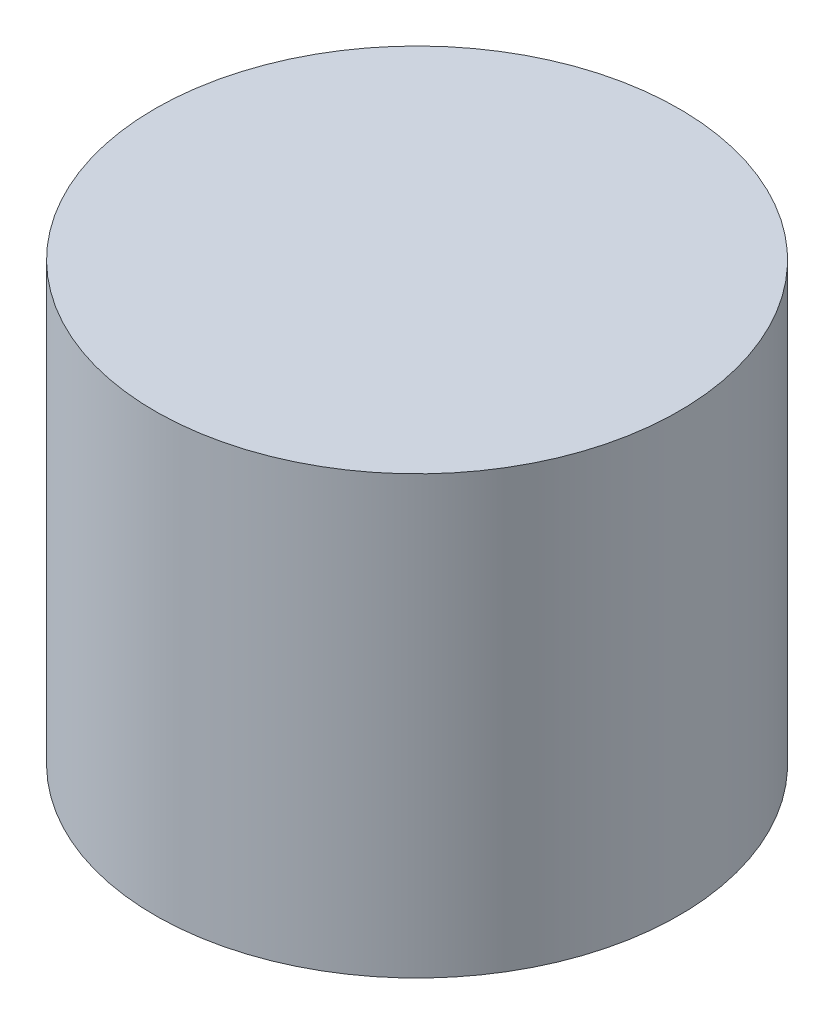
SolidWorks part; units mm, degrees
material "Custom Plastic"
ref_plane "Front Plane" through (0, 0, 0) normal (0, 0, 1) x (1, 0, 0)
ref_plane "Top Plane" through (0, 0, 0) normal (0, 1, 0) x (1, 0, 0)
ref_plane "Right Plane" through (0, 0, 0) normal (1, 0, 0) x (0, 0, -1)
sketch "Sketch1" plane through (0, 0, 0) normal (0, 0, 1) x (1, 0, 0)
  line L0 (-10.493, 8.4168) -> (-10.493, -41.5832)
  line L1 (-10.493, 8.4168) -> (19.507, 8.4168)
  line L2 (-10.493, -41.5832) -> (19.507, -41.5832)
  line L3 (19.507, 8.4168) -> (19.507, -41.5832)
  dimension "D1" = 30
  dimension "D2" = 50
revolve "Revolve1" add sketch "Sketch1" angle 360 about L3
